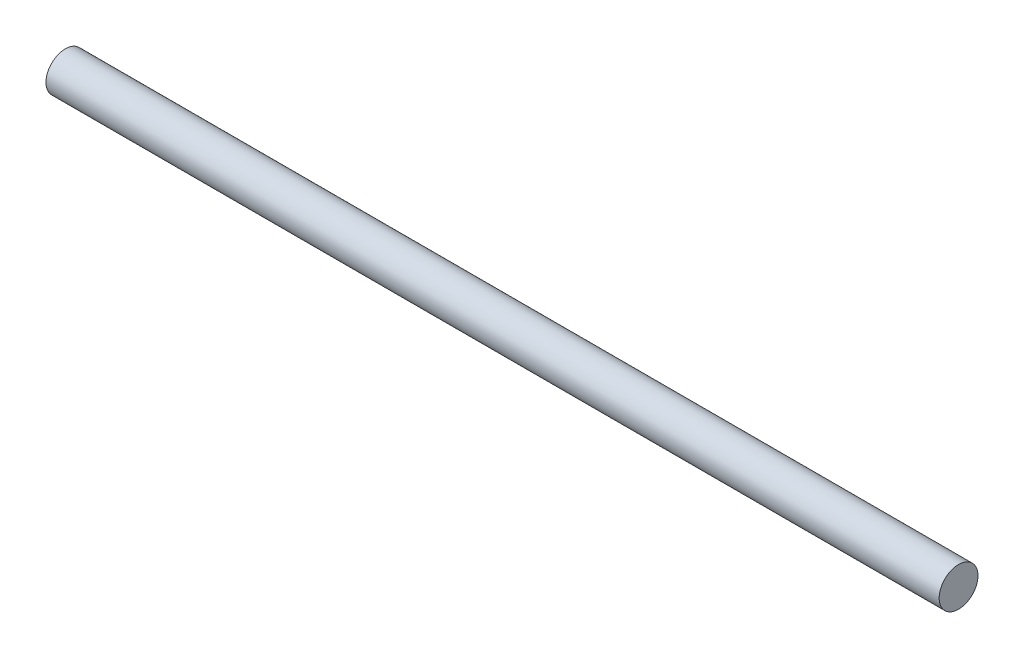
SolidWorks part; units mm, degrees
ref_plane "Front Plane" through (0, 0, 0) normal (0, 0, 1) x (1, 0, 0)
ref_plane "Top Plane" through (0, 0, 0) normal (0, 1, 0) x (1, 0, 0)
ref_plane "Right Plane" through (0, 0, 0) normal (1, 0, 0) x (0, 0, -1)
sketch "Sketch3" plane through (0, 0, 0) normal (1, 0, 0) x (0, 0, -1)
  circle A0 centre (-0.3583, 0.2483) radius 5
extrude "Boss-Extrude1" add sketch "Sketch3" along normal blind 230
